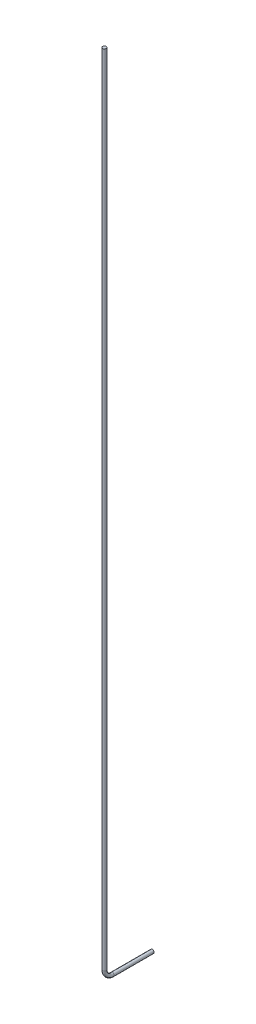
SolidWorks part; units mm, degrees
ref_plane "正面" through (0, 0, 0) normal (0, 0, 1) x (1, 0, 0)
ref_plane "平面" through (0, 0, 0) normal (0, 1, 0) x (1, 0, 0)
ref_plane "右側面" through (0, 0, 0) normal (1, 0, 0) x (0, 0, -1)
sketch "ｽｹｯﾁ1" plane through (0, 0, 0) normal (0, 0, 1) x (1, 0, 0)
  circle A0 centre (0, 0) radius 1.13
  dimension "D1" = 2.26
extrude "ﾎﾞｽ - 押し出し1" add sketch "ｽｹｯﾁ1" along normal blind 20
sketch "ｽｹｯﾁ2" plane through (0, 0, 20) normal (0, 0, 1) x (1, 0, 0)
  circle A1 centre (0, 0) radius 1.13
  circle A2 centre (0, 0) radius 1.13
  dimension "D1" = 0
sketch "ｽｹｯﾁ3" plane through (0, 0, 0) normal (1, 0, 0) x (0, 0, -1)
  line L0 (-20, 0) -> (-25, 0)
  line L1 (-20, 1.13) -> (-20, -1.13) construction
  line L2 (-30, 5) -> (-30, 505)
  line L3 (-20, 1.13) -> (-20, -1.13) construction
  arc A0 (-25, 0) -> (-30, 5) centre (-25, 5) cw
  point P8 (-30, 0)
  dimension "D2" = 5
  dimension "D1" = 10
  dimension "D3" = 500
sweep "ｽｲｰﾌﾟ1" add profiles "ｽｹｯﾁ2" path "ｽｹｯﾁ3"
